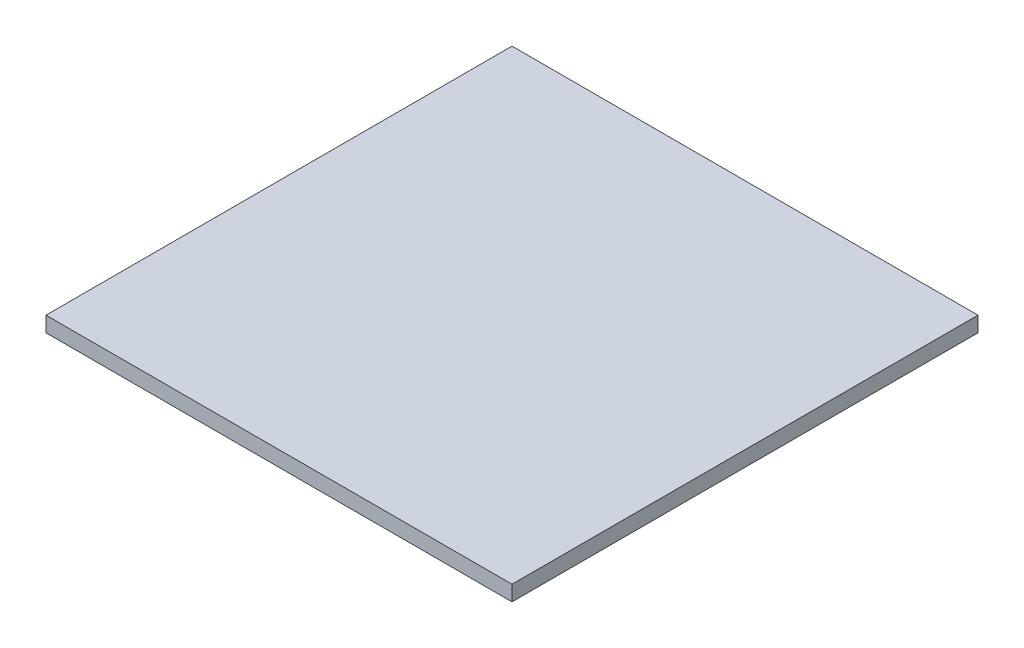
SolidWorks part; units mm, degrees
ref_plane "Front Plane" through (0, 0, 0) normal (0, 0, 1) x (1, 0, 0)
ref_plane "Top Plane" through (0, 0, 0) normal (0, 1, 0) x (1, 0, 0)
ref_plane "Right Plane" through (0, 0, 0) normal (1, 0, 0) x (0, 0, -1)
sketch "Sketch1" plane through (0, 0, 0) normal (0, 0, 1) x (1, 0, 0)
  line L1 (76.2, -2.5) -> (-76.2, -2.5)
  line L2 (76.2, -2.5) -> (76.2, 2.5)
  line L3 (76.2, 2.5) -> (-76.2, 2.5)
  line L4 (-76.2, -2.5) -> (-76.2, 2.5)
  line L5 (76.2, -2.5) -> (-76.2, 2.5) construction
  line L6 (76.2, 2.5) -> (-76.2, -2.5) construction
  point P0 (0, 0)
  dimension "D1" = 5
  dimension "D2" = 152.4
extrude "Boss-Extrude1" add sketch "Sketch1" along normal blind 152.4
